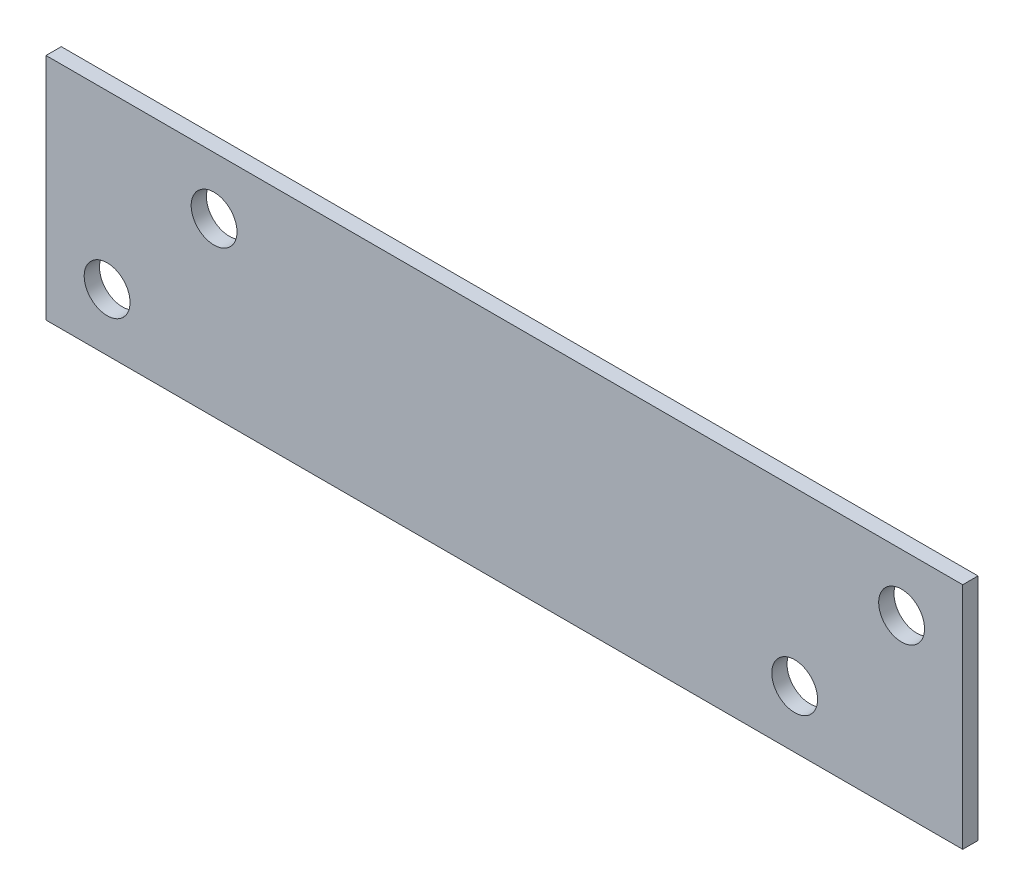
SolidWorks part; units mm, degrees
ref_plane "Plan de face" through (0, 0, 0) normal (0, 0, 1) x (1, 0, 0)
ref_plane "Plan de dessus" through (0, 0, 0) normal (0, 1, 0) x (1, 0, 0)
ref_plane "Plan de droite" through (0, 0, 0) normal (1, 0, 0) x (0, 0, -1)
sketch "Esquisse1" plane through (0, 0, 0) normal (0, 0, 1) x (1, 0, 0)
  line L0 (0, 0) -> (0, 7.5) construction
  line L1 (0, 0) -> (60, 0)
  line L2 (0, 0) -> (0, 15)
  line L3 (0, 15) -> (60, 15)
  line L4 (60, 0) -> (60, 15)
  line L5 (0, 7.5) -> (0, 15) construction
  line L6 (0, 11.25) -> (60, 11.25) construction
  line L7 (60, 11.25) -> (0, 11.25) construction
  line L8 (0, 11.25) -> (0, 3.75) construction
  line L9 (0, 3.75) -> (60, 3.75) construction
  line L10 (15, 15) -> (15, 0) construction
  line L11 (15, 0) -> (45, 0) construction
  line L12 (45, 0) -> (45, 15) construction
  circle A0 centre (11, 11.25) radius 1.5
  circle A1 centre (4, 3.75) radius 1.5
  circle A2 centre (56, 11.25) radius 1.5
  circle A3 centre (49, 3.75) radius 1.5
  point P5 (15, 15)
  point P6 (45, 15)
  dimension "D5" = 3
  dimension "D6" = 3
  dimension "D9" = 3
  dimension "D10" = 3
  dimension "D1" = 15
  dimension "D2" = 60
  dimension "D3" = 15
  dimension "D4" = 15
  dimension "D7" = 4
  dimension "D8" = 4
  dimension "D11" = 4
  dimension "D12" = 4
extrude "Boss.-Extru.1" add sketch "Esquisse1" against normal blind 1
